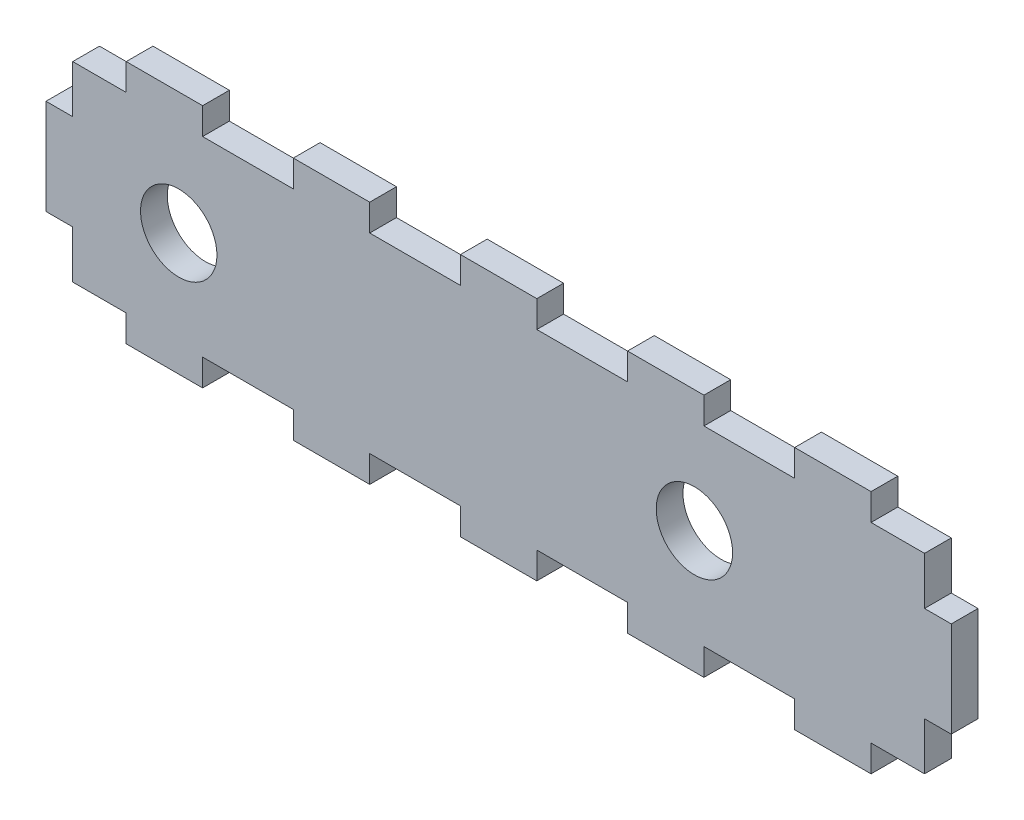
SolidWorks part; units mm, degrees
material "Фанера"
ref_plane "Front Plane" through (0, 0, 0) normal (0, 0, 1) x (1, 0, 0)
ref_plane "Top Plane" through (0, 0, 0) normal (0, 1, 0) x (1, 0, 0)
ref_plane "Right Plane" through (0, 0, 0) normal (1, 0, 0) x (0, 0, -1)
sketch "Эскиз1" plane through (0, 0, 0) normal (0, 0, 1) x (1, 0, 0)
  line L0 (39, -10) -> (44.6, -10)
  line L1 (-44.6, -10) -> (-39, -10)
  line L3 (-44.6, 10) -> (-39, 10)
  line L4 (47.4, -5) -> (47.4, 5)
  line L5 (-50, -10) -> (50, 10) construction
  line L6 (-50, 10) -> (50, -10) construction
  line L7 (31, -12.8) -> (39, -12.8)
  line L8 (31, -12.8) -> (31, -10)
  line L10 (39, -12.8) -> (39, -10)
  line L11 (31, -12.8) -> (35, -10) construction
  line L12 (35, -10) -> (39, -12.8) construction
  line L13 (13.5, -12.8) -> (13.5, -10)
  line L14 (13.5, -12.8) -> (21.5, -12.8)
  line L15 (21.5, -12.8) -> (21.5, -10)
  line L16 (-4, -12.8) -> (-4, -10)
  line L17 (-4, -12.8) -> (4, -12.8)
  line L18 (4, -12.8) -> (4, -10)
  line L19 (-21.5, -12.8) -> (-21.5, -10)
  line L20 (-21.5, -12.8) -> (-13.5, -12.8)
  line L21 (-13.5, -12.8) -> (-13.5, -10)
  line L22 (-39, -12.8) -> (-39, -10)
  line L23 (-39, -12.8) -> (-31, -12.8)
  line L24 (-31, -12.8) -> (-31, -10)
  line L25 (-31, -10) -> (-21.5, -10)
  line L26 (-13.5, -10) -> (-4, -10)
  line L27 (4, -10) -> (13.5, -10)
  line L28 (21.5, -10) -> (31, -10)
  line L29 (-36.4164, 0) -> (29.242, 0) construction
  line L30 (39, 12.8) -> (39, 10)
  line L31 (31, 12.8) -> (39, 12.8)
  line L32 (31, 12.8) -> (31, 10)
  line L33 (21.5, 12.8) -> (21.5, 10)
  line L34 (13.5, 12.8) -> (21.5, 12.8)
  line L35 (13.5, 12.8) -> (13.5, 10)
  line L36 (4, 12.8) -> (4, 10)
  line L37 (-4, 12.8) -> (4, 12.8)
  line L38 (-4, 12.8) -> (-4, 10)
  line L39 (-13.5, 12.8) -> (-13.5, 10)
  line L40 (-21.5, 12.8) -> (-13.5, 12.8)
  line L41 (-21.5, 12.8) -> (-21.5, 10)
  line L42 (-31, 12.8) -> (-31, 10)
  line L43 (-39, 12.8) -> (-31, 12.8)
  line L44 (-39, 12.8) -> (-39, 10)
  line L45 (-31, 10) -> (-21.5, 10)
  line L46 (-13.5, 10) -> (-4, 10)
  line L47 (4, 10) -> (13.5, 10)
  line L48 (21.5, 10) -> (31, 10)
  line L49 (39, 10) -> (44.6, 10)
  line L50 (44.6, 10) -> (44.6, 5)
  line L51 (44.6, 5) -> (47.4, 5)
  line L52 (44.6, -10) -> (44.6, -5)
  line L53 (44.6, -5) -> (47.4, -5)
  line L54 (0, 6.3599) -> (0, -6.9433) construction
  line L55 (-44.6, -5) -> (-47.4, -5)
  line L56 (-47.4, -5) -> (-47.4, 5)
  line L57 (-44.6, 5) -> (-47.4, 5)
  line L58 (-44.6, 10) -> (-44.6, 5)
  line L59 (-44.6, -5) -> (-44.6, -10)
  circle A0 centre (20.5, 0) radius 4
  circle A1 centre (-33.5, 0) radius 4
  point P0 (0, 0)
  point P5 (35, -10)
  point P55 (46, 5)
  dimension "D11" = 11.1
  dimension "D12" = 8
  dimension "D1" = 20
  dimension "D2" = 89.2
  dimension "D3" = 5.6
  dimension "D4" = 8
  dimension "D5" = 2.8
  dimension "D6" = 4
  dimension "D8" = 2.8
  dimension "D9" = 10
  dimension "D10" = 5
  dimension "D13" = 54
  dimension "D7" = 5
extrude "Бобышка-Вытянуть1" add sketch "Эскиз1" along normal mid plane 2.8
